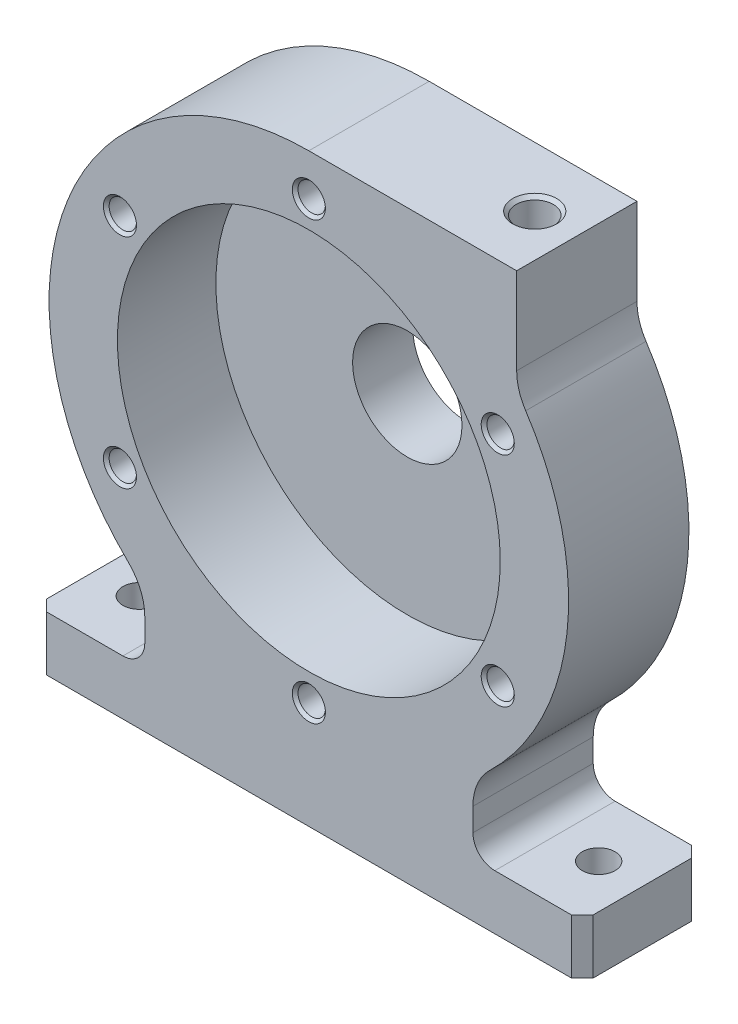
SolidWorks part; units mm, degrees
ref_plane "Front Plane" through (0, 0, 0) normal (0, 0, 1) x (1, 0, 0)
ref_plane "Top Plane" through (0, 0, 0) normal (0, 1, 0) x (1, 0, 0)
ref_plane "Right Plane" through (0, 0, 0) normal (1, 0, 0) x (0, 0, -1)
sketch "Sketch1" plane through (0, 0, 0) normal (0, 0, 1) x (1, 0, 0)
  line L0 (0, 0) -> (0, -59.5) construction
  line L1 (-50, -59.5) -> (50, -59.5)
  line L2 (50, -59.5) -> (50, -49.5)
  line L3 (50, -49.5) -> (34, -49.5)
  line L4 (30, -45.5) -> (30, -41.3068)
  line L5 (0, 47.5) -> (38, 47.5)
  line L6 (38, 47.5) -> (38, 31.6583)
  line L7 (-50, -59.5) -> (-50, -49.5)
  line L8 (-50, -49.5) -> (-34, -49.5)
  line L9 (-30, -45.5) -> (-30, -41.3068)
  arc A0 (0, 47.5) -> (-33.0435, -34.123) centre (0, 0) ccw
  arc A1 (33.0435, -34.123) -> (39.6522, 26.1525) centre (0, 0) ccw
  arc A2 (30, -41.3068) -> (33.0435, -34.123) centre (40, -41.3068) cw
  arc A3 (38, 31.6583) -> (39.6522, 26.1525) centre (48, 31.6583) ccw
  arc A4 (34, -49.5) -> (30, -45.5) centre (34, -45.5) cw
  arc A5 (-34, -49.5) -> (-30, -45.5) centre (-34, -45.5) ccw
  arc A6 (-30, -41.3068) -> (-33.0435, -34.123) centre (-40, -41.3068) ccw
  point P13 (30, -36.8273)
  dimension "D1" = 95
  dimension "D7" = 10
  dimension "D8" = 4
  dimension "D2" = 38
  dimension "D3" = 50
  dimension "D4" = 30
  dimension "D5" = 59.5
  dimension "D6" = 10
extrude "Boss-Extrude1" add sketch "Sketch1" along normal blind 22
sketch "Sketch2" plane through (0, 0, 22) normal (0, 0, 1) x (1, 0, 0)
  circle A0 centre (0, 0) radius 35
  dimension "D1" = 70
extrude "Cut-Extrude1" cut sketch "Sketch2" against normal blind 18
sketch "Sketch3" plane through (0, 0, 0) normal (0, 0, -1) x (-1, 0, 0)
  circle A0 centre (0, 0) radius 14
  dimension "D1" = 28
extrude "Boss-Extrude2" add sketch "Sketch3" along normal blind 7
fillet "Fillet1" radius 4 1 edges at (14, 0, 0)
sketch "Sketch4" plane through (0, 0, -7) normal (0, 0, -1) x (-1, 0, 0)
  circle A0 centre (0, 0) radius 10
  dimension "D1" = 20
extrude "Cut-Extrude2" cut sketch "Sketch4" against normal through all
chamfer "Chamfer1" distance 2 angle 45 4 edges at (-50, -54.5, 22) (50, -54.5, 22) (-50, -54.5, 0) (50, -54.5, 0)
sketch "Sketch5" plane through (0, 47.5, 0) normal (0, 1, 0) x (1, 0, 0)
  line L0 (38, -11) -> (0, -11) construction
  line L3 (38, -22) -> (38, 0) construction
  line L4 (0, -22) -> (0, 0) construction
hole_wizard "M8x1.25 Tapped Hole1" positions "Sketch6" profile "Sketch7" tap size "M8x1.25" standard "ANSI Metric"
sketch "Sketch6" plane through (0, 47.5, 0) normal (0, 1, 0) x (1, 0, 0)
  point P0 (30.2241, -10.9195)
  dimension "D1" = 7.7759
sketch "Sketch7" plane through (30.2241, 47.5, 10.9195) normal (1, 0, 0) x (0, 0, 1)
  line L0 (0, 0) -> (0, 31.7929)
  line L1 (0, 31.7929) -> (3.4, 29.75)
  line L2 (3.4, 29.75) -> (3.4, 0.625)
  line L3 (3.4, 0.625) -> (4.025, 0)
  line L5 (4.025, 0) -> (0, 0)
  line L6 (-3.4, 0.625) -> (-4.025, 0) construction
  line L10 (0, 31.7929) -> (-3.4, 29.75) construction
  line L11 (0, -6.35) -> (0, 107.95) construction
  dimension "Tap Drill Dia." = 6.8
  dimension "Tap Drill Depth" = 29.75
  dimension "Near C'Sink Dia." = 8.05
  dimension "Near C'Sink Angle" = 90
  dimension "Drill Angle" = 118
cosmetic thread "Hole Thread1" parameters "D1"=16, "D2"=8
sketch "Sketch8" plane through (0, 0, 22) normal (0, 0, 1) x (1, 0, 0)
  circle A0 centre (0, 0) radius 40 construction
  dimension "D1" = 80
hole_wizard "M6x1.0 Tapped Hole1" positions "Sketch9" profile "Sketch10" tap size "M6x1.0" standard "ANSI Metric"
sketch "Sketch9" plane through (0, 0, 22) normal (0, 0, 1) x (1, 0, 0)
  point P0 (0, 39.8872)
sketch "Sketch10" plane through (0, 39.8872, 22) normal (1, 0, 0) x (0, -1, 0)
  line L0 (0, 0) -> (0, 16.5022)
  line L1 (0, 16.5022) -> (2.5, 15)
  line L2 (2.5, 15) -> (2.5, 0.525)
  line L3 (2.5, 0.525) -> (3.025, 0)
  line L5 (3.025, 0) -> (0, 0)
  line L6 (-2.5, 0.525) -> (-3.025, 0) construction
  line L10 (0, 16.5022) -> (-2.5, 15) construction
  line L11 (0, -6.35) -> (0, 107.95) construction
  dimension "Tap Drill Dia." = 5
  dimension "Tap Drill Depth" = 15
  dimension "Near C'Sink Dia." = 6.05
  dimension "Near C'Sink Angle" = 90
  dimension "Drill Angle" = 118
cosmetic thread "Hole Thread2" parameters "D1"=12, "D2"=6
pattern_circular "CirPattern1" count 6 over 360 about axis through (0, 0, 0) along (0, 0, 1) of "M6x1.0 Tapped Hole1"
hole_wizard "CSK for M8 Countersunk Flat Head Screw1" positions "Sketch11" profile "Sketch12" countersink size "M8" standard "ISO"
sketch "Sketch11" plane through (0, -59.5, 0) normal (0, -1, 0) x (-1, 0, 0)
  line L0 (50, -20) -> (50, -2) construction
  line L1 (-50, -20) -> (-50, -2) construction
  point P0 (42, -11)
  point P2 (-42, -11)
  dimension "D1" = 8
  dimension "D2" = 8
sketch "Sketch12" plane through (-42, -59.5, 11) normal (1, 0, 0) x (0, 0, -1)
  line L0 (0, 0) -> (0, 21.8026)
  line L1 (0, 21.8026) -> (3, 20)
  line L2 (3, 20) -> (3, 1)
  line L3 (3, 1) -> (4, 0)
  line L5 (4, 0) -> (0, 0)
  line L6 (-3, 1) -> (-4, 0) construction
  line L10 (0, 21.8026) -> (-3, 20) construction
  line L11 (0, -6.35) -> (0, 107.95) construction
  dimension "Hole Dia." = 6
  dimension "Hole Depth" = 20
  dimension "Near C'Sink Dia." = 8
  dimension "Near C'Sink Angle" = 90
  dimension "Drill Angle" = 118
